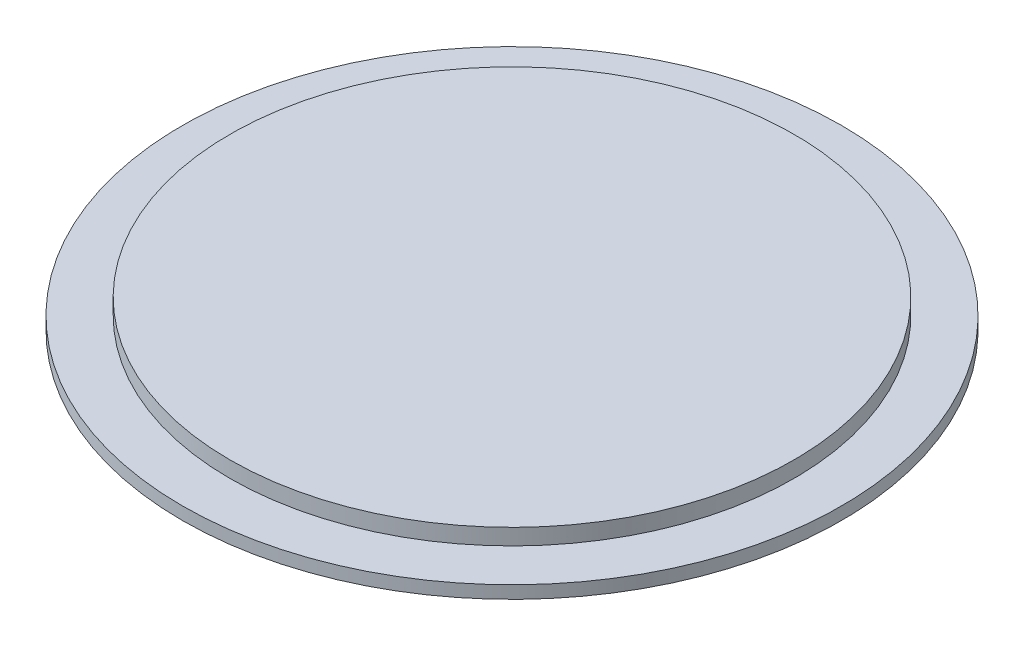
SolidWorks part; units mm, degrees
ref_plane "Front Plane" through (0, 0, 0) normal (0, 0, 1) x (1, 0, 0)
ref_plane "Top Plane" through (0, 0, 0) normal (0, 1, 0) x (1, 0, 0)
ref_plane "Right Plane" through (0, 0, 0) normal (1, 0, 0) x (0, 0, -1)
sketch "Sketch1" plane through (0, 0, 0) normal (0, 1, 0) x (1, 0, 0)
  circle A0 centre (0, 0) radius 52
  dimension "D1" = 104
extrude "Boss-Extrude1" add sketch "Sketch1" along normal blind 2
sketch "Sketch2" plane through (0, 2, 0) normal (0, 1, 0) x (1, 0, 0)
  circle A0 centre (0, 0) radius 44.5
  dimension "D1" = 89
extrude "Boss-Extrude2" add sketch "Sketch2" along normal blind 2.54
